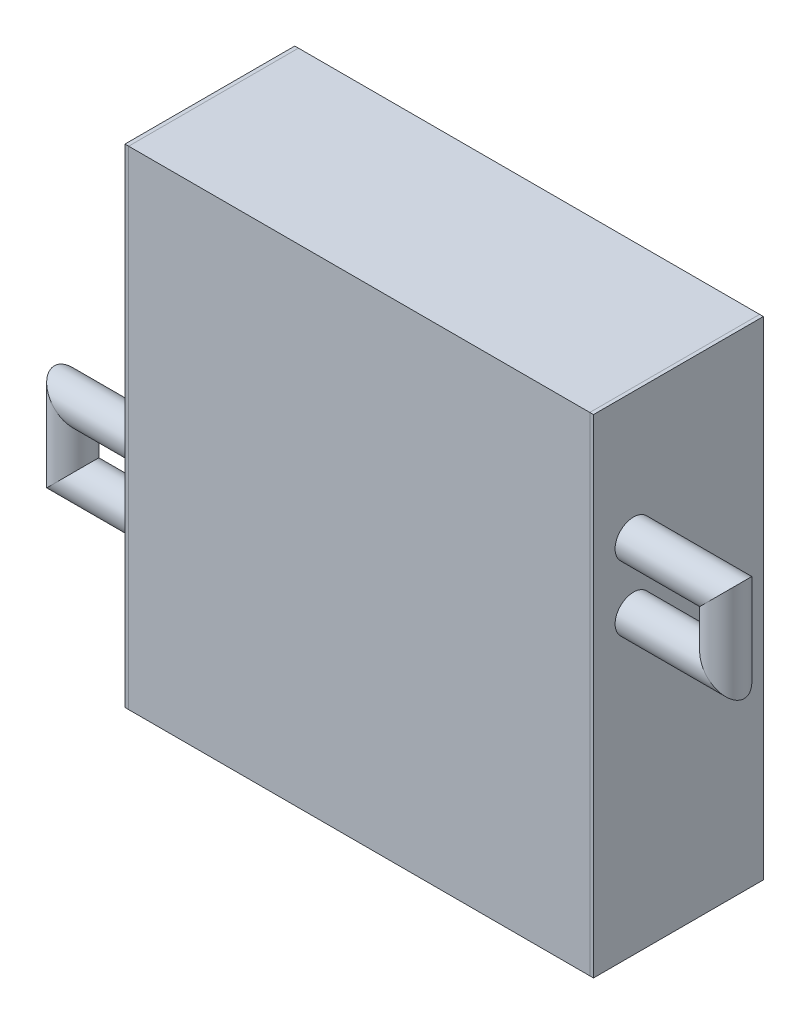
SolidWorks part; units mm, degrees
ref_plane "Front Plane" through (0, 0, 0) normal (0, 0, 1) x (1, 0, 0)
ref_plane "Top Plane" through (0, 0, 0) normal (0, 1, 0) x (1, 0, 0)
ref_plane "Right Plane" through (0, 0, 0) normal (1, 0, 0) x (0, 0, -1)
sketch "Sketch1" plane through (0, 0, 0) normal (1, 0, 0) x (0, 0, -1)
  line L0 (-145, 145) -> (-145, 255)
  line L2 (-145, 0) -> (-145, 145)
  line L3 (-145, 145) -> (0, 145) construction
  line L4 (0, 0) -> (0, 145)
  line L5 (-145, 255) -> (0, 255)
  line L6 (0, 255) -> (0, 145)
  line L7 (0, -145) -> (420.2376, 355.8197) construction
  line L8 (0, -145) -> (-93.2042, -33.9236) construction
  line L9 (94.1529, -32.793) -> (175.1688, -32.793) construction
  line L10 (-93.2042, -33.9236) -> (741.3522, 221.2259) construction
  line L11 (301.5271, 86.7579) -> (438.6224, 86.7579) construction
  line L12 (0, -145) -> (-176.7331, -199.0327) construction
  line L13 (-93.2042, -33.9236) -> (-193.8224, -153.8356) construction
  line L14 (274.6455, 249.3185) -> (274.6455, -80.6815)
  line L15 (274.6455, -80.6815) -> (168.3686, 167.5225)
  arc A0 (0, -145) -> (-145, 0) centre (0, 0) cw
  parabola Q0 (0, 0) -> (300.3031, 267.8046) focus (0, -145) apex (-49.0614, -159.9996)
  parabola Q1 (0, -145) -> (593.7614, 75.583) focus (-93.2042, -33.9236) apex (-147.8987, -99.1059)
  dimension "D1" = 145
  dimension "D2" = 110
  dimension "D3" = 50
  dimension "D4" = 17
  dimension "D5" = 80
  dimension "D6" = 330
  dimension "D7" = 270
sketch "Sketch2" plane through (0, 0, 0) normal (1, 0, 0) x (0, 0, -1)
  line L0 (-145, 145) -> (0, 145) construction
  line L1 (0, 255) -> (0, 145) construction
  line L2 (-145, 255) -> (0, 255) construction
  line L3 (-145, 145) -> (-145, 255) construction
  line L4 (274.6455, -80.6815) -> (168.3686, 167.5225) construction
  line L5 (274.6455, 249.3185) -> (274.6455, -80.6815) construction
  line L6 (0, 0) -> (0, 145) construction
  line L7 (-145, 0) -> (-145, 145) construction
  line L8 (-145, 145) -> (0, 145) construction
  line L9 (0, 255) -> (0, 145)
  line L10 (-145, 255) -> (0, 255)
  line L11 (-145, 145) -> (-145, 255)
  line L12 (274.6455, -80.6815) -> (168.3686, 167.5225)
  line L13 (274.6455, 249.3185) -> (274.6455, -80.6815) construction
  line L14 (0, 0) -> (0, 145)
  line L15 (-145, 0) -> (-145, 145)
  line L16 (-145.6, 0) -> (-145.6, 145)
  line L20 (0.6, 1.8139) -> (0.6, 145)
  line L21 (274.2922, 249.8034) -> (274.6455, 249.3185)
  line L22 (274.6455, -80.6815) -> (274.8642, -81.2403)
  line L23 (168.3686, 167.5225) -> (172.0457, 169.097)
  line L24 (168.3686, 167.5225) -> (274.6455, -80.6815)
  line L25 (172.0457, 169.097) -> (278.3226, -79.1071)
  line L26 (274.6455, -80.6815) -> (278.3226, -79.1071)
  line L27 (0, 145) -> (0.6, 145)
  line L28 (-145, 145) -> (-145.6, 145)
  line L29 (-155, 145) -> (-155, 265)
  line L30 (0.6, 255.6) -> (0.6, 145) construction
  line L31 (-145.6, 255.6) -> (0.6, 255.6) construction
  line L32 (-145.6, 145) -> (-145.6, 255.6) construction
  line L33 (-155, 265) -> (10, 265)
  line L34 (10, 265) -> (10, 145)
  line L35 (-155, 145) -> (-145, 145)
  line L36 (10, 145) -> (0, 145)
  line L38 (0, 145) -> (-145, 145)
  line L39 (0, 145) -> (0, 144.7)
  line L40 (0, 144.7) -> (-145, 144.7)
  line L41 (-145, 145) -> (-145, 144.7)
  arc A0 (-145, 0) -> (0, -145) centre (0, 0) ccw construction
  arc A1 (-145, 0) -> (0, -145) centre (0, 0) ccw
  arc A2 (-145.6, 0) -> (0, -145.6) centre (0, 0) ccw
  parabola Q0 (0, -145) -> (593.7614, 75.583) focus (-93.2042, -33.9236) apex (-147.8987, -99.1059) construction
  parabola Q1 (0, 0) -> (300.3031, 267.8046) focus (0, -145) apex (-49.0614, -159.9996) construction
  parabola Q2 (0, -145) -> (274.6455, -80.6815) focus (-93.2042, -33.9236) apex (-147.8987, -99.1059)
  parabola Q3 (0, 0) -> (274.6455, 249.3185) focus (0, -145) apex (-49.0614, -159.9996)
  spline S0 degree 1 poles (0, -145.6) (274.8642, -81.2403) knots 0 0 1 1 construction
  spline S1 degree 1 poles (0.6, 1.8139) (274.2922, 249.8034) knots 0 0 1 1 construction
  spline S2 degree 3 poles (274.8642, -81.2403) (273.1576, -81.9083) (269.7338, -83.2415) (262.9417, -85.8581) (254.5103, -89.0531) (244.501, -92.7603) (231.2945, -97.5361) (215.05, -103.1917) (195.9774, -109.4761) (177.3259, -115.2579) (153.0186, -122.2971) (123.6866, -129.8396) (90.1715, -136.8804) (63.6442, -141.072) (43.2642, -143.4196) (28.3972, -144.6775) (16.3662, -145.3064) (6.9341, -145.5581) (2.32, -145.6) (0, -145.6) knots 0.50387 0.50387 0.50387 0.50387 0.503942 0.504013 0.504156 0.5043 0.504443 0.504729 0.505015 0.505302 0.505588 0.506161 0.506734 0.507306 0.507593 0.507879 0.508165 0.508308 0.508452 0.508452 0.508452 0.508452
  spline S3 degree 3 poles (0.6, 1.8139) (1.4319, 2.9295) (3.0981, 5.1446) (6.5223, 9.6202) (10.937, 15.2496) (16.4614, 22.0765) (24.1255, 31.2688) (34.2669, 42.9303) (47.3338, 57.1972) (61.2981, 71.7376) (81.1138, 91.4895) (108.1271, 116.8637) (138.1321, 143.1509) (163.9312, 164.7288) (184.1782, 181.1862) (205.3228, 197.9178) (223.6912, 212.0892) (238.8352, 223.5637) (250.4165, 232.2373) (260.2579, 239.5249) (268.2359, 245.3839) (272.2758, 248.3346) (274.2922, 249.8034) knots 0.504877 0.504877 0.504877 0.504877 0.504963 0.505049 0.50522 0.505391 0.505563 0.505905 0.506248 0.50659 0.506933 0.507618 0.508303 0.508646 0.508989 0.509331 0.509674 0.509845 0.510016 0.510188 0.510273 0.510359 0.510359 0.510359 0.510359
  dimension "D2" = 4
  dimension "D4" = 0.3
  dimension "D1" = 0.6
  dimension "D3" = 10
sketch "Sketch3" plane through (0, 0, 0) normal (1, 0, 0) x (0, 0, -1)
  line L0 (274.6455, -80.6815) -> (168.3686, 167.5225) construction
  line L1 (168.3686, 167.5225) -> (172.0457, 169.097) construction
  line L2 (172.0457, 169.097) -> (278.3226, -79.1071) construction
  line L3 (274.6455, -80.6815) -> (278.3226, -79.1071) construction
  line L4 (168.3686, 167.5225) -> (274.6455, -80.6815) construction
  line L5 (0, 255) -> (0, 145) construction
  line L6 (-145, 255) -> (0, 255) construction
  line L7 (-145, 145) -> (-145, 255) construction
  line L8 (-145, 0) -> (-145, 145) construction
  line L9 (-145, 145) -> (-145.6, 145) construction
  line L10 (-145.6, 0) -> (-145.6, 145) construction
  line L11 (274.6455, -80.6815) -> (274.8642, -81.2403) construction
  line L12 (-155, 145) -> (-145, 145) construction
  line L13 (-155, 145) -> (-155, 265) construction
  line L14 (-155, 265) -> (10, 265) construction
  line L15 (10, 265) -> (10, 145) construction
  line L16 (10, 145) -> (0, 145) construction
  line L17 (0, 145) -> (-145, 145) construction
  line L18 (0, 145) -> (0, 144.7) construction
  line L19 (0, 144.7) -> (-145, 144.7) construction
  line L20 (-145, 145) -> (-145, 144.7) construction
  line L21 (0, 0) -> (0, 145) construction
  line L22 (274.2922, 249.8034) -> (274.6455, 249.3185) construction
  line L23 (0.6, 1.8139) -> (0.6, 145) construction
  line L24 (0, 145) -> (0.6, 145) construction
  line L25 (274.6455, -80.6815) -> (168.3686, 167.5225)
  line L26 (168.3686, 167.5225) -> (172.0457, 169.097)
  line L27 (172.0457, 169.097) -> (278.3226, -79.1071)
  line L28 (274.6455, -80.6815) -> (278.3226, -79.1071)
  line L29 (168.3686, 167.5225) -> (274.6455, -80.6815)
  line L30 (0, 255) -> (0, 145)
  line L31 (-145, 255) -> (0, 255)
  line L32 (-145, 145) -> (-145, 255)
  line L33 (-145, 0) -> (-145, 145)
  line L34 (-145, 145) -> (-145.6, 145)
  line L35 (-145.6, 0) -> (-145.6, 145)
  line L36 (274.6455, -80.6815) -> (274.8642, -81.2403)
  line L37 (-155, 145) -> (-145, 145)
  line L38 (-155, 145) -> (-155, 265)
  line L39 (-155, 265) -> (10, 265)
  line L40 (10, 265) -> (10, 145)
  line L41 (10, 145) -> (0, 145)
  line L42 (0, 145) -> (-145, 145)
  line L43 (0, 145) -> (0, 144.7)
  line L44 (0, 144.7) -> (-145, 144.7)
  line L45 (-145, 145) -> (-145, 144.7)
  line L46 (0, 0) -> (0, 145)
  line L47 (274.2922, 249.8034) -> (274.6455, 249.3185)
  line L48 (0.6, 1.8139) -> (0.6, 145)
  line L49 (0, 145) -> (0.6, 145)
  line L50 (-155, 575) -> (-155, 695)
  line L51 (-145, 575) -> (-145, 685)
  line L52 (-155, 695) -> (10, 695)
  line L53 (-145, 685) -> (0, 685)
  line L54 (10, 695) -> (10, 575)
  line L55 (0, 685) -> (0, 575)
  line L56 (10, 575) -> (0, 575)
  line L57 (0.6, 431.8139) -> (0.6, 575)
  line L58 (0, 430) -> (0, 575)
  line L59 (0, 574.7) -> (-145, 574.7)
  line L60 (-145, 430) -> (-145, 575)
  line L61 (-145.6, 430) -> (-145.6, 575)
  line L62 (-155, 575) -> (-145, 575)
  line L63 (274.6455, 349.3185) -> (274.8642, 348.7597)
  line L64 (274.6455, 349.3185) -> (278.3226, 350.8929)
  line L65 (274.6455, 349.3185) -> (168.3686, 597.5225)
  line L66 (172.0457, 599.097) -> (278.3226, 350.8929)
  line L67 (168.3686, 597.5225) -> (172.0457, 599.097)
  line L68 (274.2922, 679.8034) -> (274.6455, 679.3185)
  line L69 (0, 575) -> (-145, 575)
  line L70 (-155, 1005) -> (-155, 1125)
  line L71 (-145, 1005) -> (-145, 1115)
  line L72 (-155, 1125) -> (10, 1125)
  line L73 (-145, 1115) -> (0, 1115)
  line L74 (10, 1125) -> (10, 1005)
  line L75 (0, 1115) -> (0, 1005)
  line L76 (10, 1005) -> (0, 1005)
  line L77 (0.6, 861.8139) -> (0.6, 1005)
  line L78 (0, 860) -> (0, 1005)
  line L79 (0, 1004.7) -> (-145, 1004.7)
  line L80 (-145, 860) -> (-145, 1005)
  line L81 (-145.6, 860) -> (-145.6, 1005)
  line L82 (-155, 1005) -> (-145, 1005)
  line L83 (274.6455, 779.3185) -> (274.8642, 778.7597)
  line L84 (274.6455, 779.3185) -> (278.3226, 780.8929)
  line L85 (274.6455, 779.3185) -> (168.3686, 1027.5225)
  line L86 (172.0457, 1029.097) -> (278.3226, 780.8929)
  line L87 (168.3686, 1027.5225) -> (172.0457, 1029.097)
  line L88 (274.2922, 1109.8034) -> (274.6455, 1109.3185)
  line L89 (0, 1005) -> (-145, 1005)
  arc A0 (-145, 0) -> (0, -145) centre (0, 0) ccw construction
  arc A1 (-145.6, 0) -> (0, -145.6) centre (0, 0) ccw construction
  arc A2 (-145, 0) -> (0, -145) centre (0, 0) ccw
  arc A3 (-145.6, 0) -> (0, -145.6) centre (0, 0) ccw
  arc A4 (-145, 430) -> (0, 285) centre (0, 430) ccw
  arc A5 (-145.6, 430) -> (0, 284.4) centre (0, 430) ccw
  arc A6 (-145, 860) -> (0, 715) centre (0, 860) ccw
  arc A7 (-145.6, 860) -> (0, 714.4) centre (0, 860) ccw
  parabola Q0 (0, -145) -> (274.6455, -80.6815) focus (-93.2042, -33.9236) apex (-147.8987, -99.1059) construction
  parabola Q1 (0, 0) -> (274.6455, 249.3185) focus (0, -145) apex (-49.0614, -159.9996) construction
  parabola Q2 (0, -145) -> (274.6455, -80.6815) focus (-93.2042, -33.9236) apex (-147.8987, -99.1059)
  parabola Q3 (0, 0) -> (274.6455, 249.3185) focus (0, -145) apex (-49.0614, -159.9996)
  parabola Q4 (0, 430) -> (274.6455, 679.3185) focus (0, 285) apex (-49.0614, 270.0004)
  parabola Q5 (0, 285) -> (274.6455, 349.3185) focus (-93.2042, 396.0764) apex (-147.8987, 330.8941)
  parabola Q6 (0, 860) -> (274.6455, 1109.3185) focus (0, 715) apex (-49.0614, 700.0004)
  parabola Q7 (0, 715) -> (274.6455, 779.3185) focus (-93.2042, 826.0764) apex (-147.8987, 760.8941)
  spline S0 degree 3 poles (-2532.6565, -1138.1182) (517.166, 27.2131) (377.0621, -41.8945) (262.9417, -85.8581) (254.5103, -89.0531) (244.501, -92.7603) (231.2945, -97.5361) (215.05, -103.1917) (195.9774, -109.4761) (177.3259, -115.2579) (153.0186, -122.2971) (123.6866, -129.8396) (90.1715, -136.8804) (63.6442, -141.072) (43.2642, -143.4196) (28.3972, -144.6775) (16.3662, -145.3064) (-89.7923, -148.1384) (-144.0863, -112.0401) (-2997.9045, -39.5411) knots 0.499345 0.499345 0.499345 0.499345 0.503942 0.504013 0.504156 0.5043 0.504443 0.504729 0.505015 0.505302 0.505588 0.506161 0.506734 0.507306 0.507593 0.507879 0.508165 0.508308 0.514325 0.514325 0.514325 0.514325 only from (274.8642, -81.2403) to (0, -145.6) construction
  spline S1 degree 3 poles (-1751.4871, -2433.1925) (-55.1342, -100.2952) (-43.2482, -55.4331) (6.5223, 9.6202) (10.937, 15.2496) (16.4614, 22.0765) (24.1255, 31.2688) (34.2669, 42.9303) (47.3338, 57.1972) (61.2981, 71.7376) (81.1138, 91.4895) (108.1271, 116.8637) (138.1321, 143.1509) (163.9312, 164.7288) (184.1782, 181.1862) (205.3228, 197.9178) (223.6912, 212.0892) (238.8352, 223.5637) (250.4165, 232.2373) (260.2579, 239.5249) (377.9568, 325.9622) (533.0374, 426.7515) (-2133.1319, -1539.7711) knots 0.50024 0.50024 0.50024 0.50024 0.504963 0.505049 0.50522 0.505391 0.505563 0.505905 0.506248 0.50659 0.506933 0.507618 0.508303 0.508646 0.508989 0.509331 0.509674 0.509845 0.510016 0.510188 0.510273 0.515071 0.515071 0.515071 0.515071 only from (0.6, 1.8139) to (274.2922, 249.8034) construction
  spline S2 degree 3 poles (274.8642, -81.2403) (273.1576, -81.9083) (269.7338, -83.2415) (262.9417, -85.8581) (254.5103, -89.0531) (244.501, -92.7603) (231.2945, -97.5361) (215.05, -103.1917) (195.9774, -109.4761) (177.3259, -115.2579) (153.0186, -122.2971) (123.6866, -129.8396) (90.1715, -136.8804) (63.6442, -141.072) (43.2642, -143.4196) (28.3972, -144.6775) (16.3662, -145.3064) (6.9341, -145.5581) (2.32, -145.6) (0, -145.6) knots 0.50387 0.50387 0.50387 0.50387 0.503942 0.504013 0.504156 0.5043 0.504443 0.504729 0.505015 0.505302 0.505588 0.506161 0.506734 0.507306 0.507593 0.507879 0.508165 0.508308 0.508452 0.508452 0.508452 0.508452
  spline S3 degree 3 poles (0.6, 1.8139) (1.4319, 2.9295) (3.0981, 5.1446) (6.5223, 9.6202) (10.937, 15.2496) (16.4614, 22.0765) (24.1255, 31.2688) (34.2669, 42.9303) (47.3338, 57.1972) (61.2981, 71.7376) (81.1138, 91.4895) (108.1271, 116.8637) (138.1321, 143.1509) (163.9312, 164.7288) (184.1782, 181.1862) (205.3228, 197.9178) (223.6912, 212.0892) (238.8352, 223.5637) (250.4165, 232.2373) (260.2579, 239.5249) (268.2359, 245.3839) (272.2758, 248.3346) (274.2922, 249.8034) knots 0.504877 0.504877 0.504877 0.504877 0.504963 0.505049 0.50522 0.505391 0.505563 0.505905 0.506248 0.50659 0.506933 0.507618 0.508303 0.508646 0.508989 0.509331 0.509674 0.509845 0.510016 0.510188 0.510273 0.510359 0.510359 0.510359 0.510359
  spline S4 degree 3 poles (0.6, 431.8139) (1.4319, 432.9295) (3.0981, 435.1446) (6.5223, 439.6202) (10.937, 445.2496) (16.4614, 452.0765) (24.1255, 461.2688) (34.2669, 472.9303) (47.3338, 487.1972) (61.2981, 501.7376) (81.1138, 521.4895) (108.1271, 546.8637) (138.1321, 573.1509) (163.9312, 594.7288) (184.1782, 611.1862) (205.3228, 627.9178) (223.6912, 642.0892) (238.8352, 653.5637) (250.4165, 662.2373) (260.2579, 669.5249) (268.2359, 675.3839) (272.2758, 678.3346) (274.2922, 679.8034) knots 0.504877 0.504877 0.504877 0.504877 0.504963 0.505049 0.50522 0.505391 0.505563 0.505905 0.506248 0.50659 0.506933 0.507618 0.508303 0.508646 0.508989 0.509331 0.509674 0.509845 0.510016 0.510188 0.510273 0.510359 0.510359 0.510359 0.510359
  spline S5 degree 3 poles (274.8642, 348.7597) (273.1576, 348.0917) (269.7338, 346.7585) (262.9417, 344.1419) (254.5103, 340.9469) (244.501, 337.2397) (231.2945, 332.4639) (215.05, 326.8083) (195.9774, 320.5239) (177.3259, 314.7421) (153.0186, 307.7029) (123.6866, 300.1604) (90.1715, 293.1196) (63.6442, 288.928) (43.2642, 286.5804) (28.3972, 285.3225) (16.3662, 284.6936) (6.9341, 284.4419) (2.32, 284.4) (0, 284.4) knots 0.50387 0.50387 0.50387 0.50387 0.503942 0.504013 0.504156 0.5043 0.504443 0.504729 0.505015 0.505302 0.505588 0.506161 0.506734 0.507306 0.507593 0.507879 0.508165 0.508308 0.508452 0.508452 0.508452 0.508452
  spline S6 degree 3 poles (0.6, 861.8139) (1.4319, 862.9295) (3.0981, 865.1446) (6.5223, 869.6202) (10.937, 875.2496) (16.4614, 882.0765) (24.1255, 891.2688) (34.2669, 902.9303) (47.3338, 917.1972) (61.2981, 931.7376) (81.1138, 951.4895) (108.1271, 976.8637) (138.1321, 1003.1509) (163.9312, 1024.7288) (184.1782, 1041.1862) (205.3228, 1057.9178) (223.6912, 1072.0892) (238.8352, 1083.5637) (250.4165, 1092.2373) (260.2579, 1099.5249) (268.2359, 1105.3839) (272.2758, 1108.3346) (274.2922, 1109.8034) knots 0.504877 0.504877 0.504877 0.504877 0.504963 0.505049 0.50522 0.505391 0.505563 0.505905 0.506248 0.50659 0.506933 0.507618 0.508303 0.508646 0.508989 0.509331 0.509674 0.509845 0.510016 0.510188 0.510273 0.510359 0.510359 0.510359 0.510359
  spline S7 degree 3 poles (274.8642, 778.7597) (273.1576, 778.0917) (269.7338, 776.7585) (262.9417, 774.1419) (254.5103, 770.9469) (244.501, 767.2397) (231.2945, 762.4639) (215.05, 756.8083) (195.9774, 750.5239) (177.3259, 744.7421) (153.0186, 737.7029) (123.6866, 730.1604) (90.1715, 723.1196) (63.6442, 718.928) (43.2642, 716.5804) (28.3972, 715.3225) (16.3662, 714.6936) (6.9341, 714.4419) (2.32, 714.4) (0, 714.4) knots 0.50387 0.50387 0.50387 0.50387 0.503942 0.504013 0.504156 0.5043 0.504443 0.504729 0.505015 0.505302 0.505588 0.506161 0.506734 0.507306 0.507593 0.507879 0.508165 0.508308 0.508452 0.508452 0.508452 0.508452
  point P13 (0, 0)
  point P17 (0, 0)
  dimension "D1" = 3
extrude "Boss-Extrude1" add sketch "Sketch3" against normal blind 1250 contours S3 L48 L41 L43 L46 Q3 L47 | L41 L40 L39 L38 L37 L34 L32 L31 L30 | L44 L43 L42 L33 | S2 L36 Q2 A2 L33 L34 L35 A3 | L25 L28 L27 L26 | S5 L63 Q5 A4 L60 L62 L61 A5 | L67 L65 L64 L66 | S4 L57 L56 L58 Q4 L68 | L50 L62 L51 L53 L55 L56 L54 L52 | L58 L69 L60 L59 | L87 L85 L84 L86 | S7 L83 Q7 A6 L80 L82 L81 A7 | S6 L77 L76 L78 Q6 L88 | L78 L89 L80 L79 | L70 L82 L71 L73 L75 L76 L74 L72
sketch "Sketch4" plane through (0, 0, 0) normal (1, 0, 0) x (0, 0, -1)
  line L0 (-155, 1125) -> (10, 1125) construction
  line L1 (-180, 1150) -> (278.3226, 1150)
  line L2 (-180, 1150) -> (-180, -170.6)
  line L3 (-180, -170.6) -> (278.3226, -170.6)
  line L4 (278.3226, 1150) -> (278.3226, 1109.3185)
  line L5 (-155, 1005) -> (-155, 1125) construction
  line L6 (274.6455, 1109.3185) -> (278.3226, 1109.3185)
  line L7 (274.6455, 679.3185) -> (278.3226, 679.3185)
  line L8 (274.6455, 249.3185) -> (278.3226, 249.3185)
  line L9 (278.3226, 679.3185) -> (278.3226, 780.8929)
  line L10 (278.3226, -170.6) -> (278.3226, -79.1071)
  line L11 (278.3226, 249.3185) -> (278.3226, 350.8929)
  line L12 (274.6455, 1108.3185) -> (279.3226, 1108.3185)
  line L13 (279.3226, 1151) -> (279.3226, 1108.3185)
  line L14 (-181, 1151) -> (279.3226, 1151)
  line L15 (-181, 1151) -> (-181, -171.6)
  line L16 (-181, -171.6) -> (279.3226, -171.6)
  line L17 (279.3226, -171.6) -> (279.3226, -79.1071)
  line L18 (274.6455, 248.3185) -> (279.3226, 248.3185)
  line L19 (279.3226, 248.3185) -> (279.3226, 350.8929)
  line L20 (274.6455, 678.3185) -> (279.3226, 678.3185)
  line L21 (279.3226, 678.3185) -> (279.3226, 780.8929)
  line L22 (274.6455, 1108.3185) -> (274.6455, 1109.3185)
  line L23 (278.3226, 780.8929) -> (279.3226, 780.8929)
  line L24 (274.6455, 678.3185) -> (274.6455, 679.3185)
  line L25 (279.3226, 350.8929) -> (278.3226, 350.8929)
  line L26 (274.6455, 248.3185) -> (274.6455, 249.3185)
  line L27 (279.3226, -79.1071) -> (278.3226, -79.1071)
  dimension "D1" = 25
  dimension "D2" = 25
  dimension "D3" = 25
  dimension "D4" = 1
extrude "Boss-Extrude2" add sketch "Sketch4" against normal blind 1250 separate body
sketch "Sketch5" plane through (0, 0, 0) normal (1, 0, 0) x (0, 0, -1)
  line L1 (-181, 1151) -> (279.3226, 1151)
  line L2 (-181, 1151) -> (-181, -171.6)
  line L3 (-181, -171.6) -> (279.3226, -171.6)
  line L4 (279.3226, 1151) -> (279.3226, -171.6)
extrude "Boss-Extrude3" add sketch "Sketch5" along normal blind 10 separate body
sketch "Sketch6" plane through (-1250, 0, 0) normal (-1, 0, 0) x (0, 0, 1)
  line L4 (181, 1151) -> (-279.3226, 1151)
  line L5 (-279.3226, 1151) -> (-279.3226, -171.6)
  line L6 (-279.3226, -171.6) -> (181, -171.6)
  line L7 (181, -171.6) -> (181, 1151)
  line L8 (181, 1151) -> (-279.3226, 1151)
  line L9 (-279.3226, 1151) -> (-279.3226, -171.6)
  line L10 (-279.3226, -171.6) -> (181, -171.6)
  line L11 (181, -171.6) -> (181, 1151)
  dimension "D1" = 0
extrude "Boss-Extrude5" add sketch "Sketch6" along normal blind 10 separate body
sketch "Sketch7" plane through (10, 0, 0) normal (1, 0, 0) x (0, 0, -1)
  line L0 (-145, 145) -> (-145, 255) construction
  line L2 (-145, 255) -> (0, 255) construction
  circle A0 centre (-72.5, 200) radius 50
  circle A1 centre (-72.5, -53.7009) radius 50
  circle A2 centre (-72.5, 630) radius 50
  circle A3 centre (-72.5, 376.2991) radius 50
  circle A4 centre (-72.5, 1060) radius 50
  circle A5 centre (-72.5, 806.2991) radius 50
  dimension "D1" = 100
  dimension "D2" = 100
  dimension "D3" = 72.5
  dimension "D4" = 55
  dimension "D5" = 3
sketch "Sketch8" plane through (-1260, 0, 0) normal (-1, 0, 0) x (0, 0, 1)
  circle A1 centre (72.5, 1060) radius 50
  circle A2 centre (72.5, 1060) radius 50
  circle A3 centre (72.5, 376.2991) radius 50
  circle A4 centre (72.5, 376.2991) radius 50
  circle A5 centre (72.5, 630) radius 50
  circle A6 centre (72.5, 630) radius 50
  circle A7 centre (72.5, -53.7009) radius 50
  circle A8 centre (72.5, -53.7009) radius 50
  circle A9 centre (72.5, 200) radius 50
  circle A10 centre (72.5, 200) radius 50
  circle A11 centre (72.5, 806.2991) radius 50
  circle A12 centre (72.5, 806.2991) radius 50
  dimension "D1" = 0
  dimension "D2" = 0
  dimension "D3" = 0
  dimension "D4" = 0
  dimension "D5" = 0
  dimension "D6" = 0
ref_plane "Plane1" through (0, 0, 72.5) normal (0, 0, 1) x (1, 0, 0)
sketch "Sketch9" plane through (0, 0, 72.5) normal (0, 0, 1) x (1, 0, 0)
  line L0 (-1260, 200) -> (-1510, 200)
  line L2 (-1260, 250) -> (-1260, 150) construction
  line L3 (-1510, 200) -> (-1510, 376.2991)
  line L5 (-1510, 376.2991) -> (-1260, 376.2991)
  line L6 (-1260, 426.2991) -> (-1260, 326.2991) construction
  dimension "D1" = 250
sketch "Sketch10" plane through (-1260, 0, 0) normal (-1, 0, 0) x (0, 0, 1)
  circle A1 centre (72.5, 200) radius 50 construction
  circle A3 centre (72.5, 200) radius 50
sweep "Sweep3" add profiles "Sketch10" path "Sketch9"
sketch "Sketch11" plane through (0, 0, 72.5) normal (0, 0, 1) x (1, 0, 0)
  line L0 (10, 630) -> (260, 630)
  line L1 (260, 630) -> (260, 806.2991)
  line L2 (260, 806.2991) -> (10, 806.2991)
  dimension "D1" = 250
sketch "Sketch12" plane through (10, 0, 0) normal (1, 0, 0) x (0, 0, -1)
  circle A0 centre (-72.5, 630) radius 50 construction
  circle A1 centre (-72.5, 630) radius 50
sweep "Sweep4" add profiles "Sketch12" path "Sketch11"
